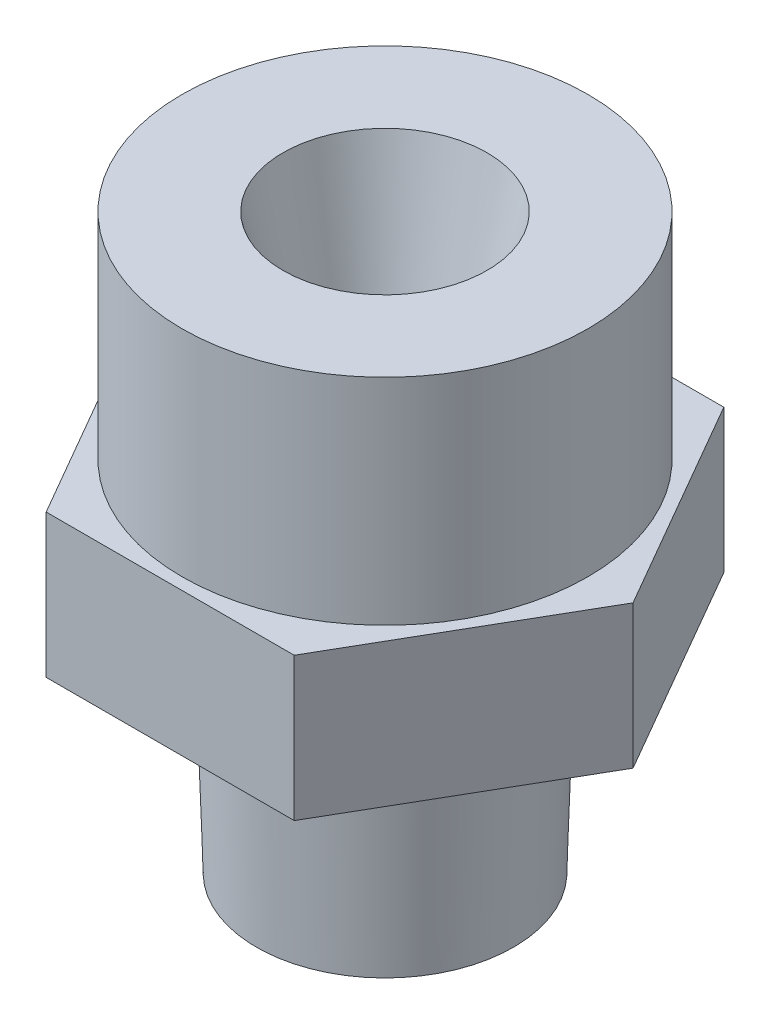
SolidWorks part; units mm, degrees
material "AISI 316 Annealed Stainless Steel Bar (SS)"
ref_plane "Front Plane" through (0, 0, 0) normal (0, 0, 1) x (1, 0, 0)
ref_plane "Top Plane" through (0, 0, 0) normal (0, 1, 0) x (1, 0, 0)
ref_plane "Right Plane" through (0, 0, 0) normal (1, 0, 0) x (0, 0, -1)
sketch "Sketch1" plane through (0, 0, 0) normal (0, 1, 0) x (1, 0, 0)
  circle A1 centre (0, 0) radius 9
  dimension "D2" = 18
extrude "Boss-Extrude1" add sketch "Sketch1" along normal blind 9.525
sketch "Sketch4" plane through (0, 0, 0) normal (0, -1, 0) x (1, 0, 0)
  circle A0 centre (0, 0) radius 3.175
  dimension "D1" = 6.35
extrude "Cut-Extrude1" cut sketch "Sketch4" against normal blind 3.175
sketch "Sketch5" plane through (0, 3.175, 0) normal (0, -1, 0) x (-1, 0, 0)
  circle A0 centre (0, 0) radius 3.175
  circle A1 centre (0, 0) radius 3.175 construction
extrude "Cut-Extrude2" cut sketch "Sketch5" against normal through all draft 12 draft outward yes
sketch "Sketch6" plane through (0, 0, 0) normal (0, -1, 0) x (1, 0, 0)
  line L1 (-10.9985, 0) -> (-5.4993, -9.525)
  line L2 (-5.4993, -9.525) -> (5.4993, -9.525)
  line L3 (5.4993, -9.525) -> (10.9985, 0)
  line L4 (10.9985, 0) -> (5.4993, 9.525)
  line L5 (5.4993, 9.525) -> (-5.4993, 9.525)
  line L6 (-5.4993, 9.525) -> (-10.9985, 0)
  circle A0 centre (0, 0) radius 9.525 construction
  circle A1 centre (0, 0) radius 3.175
  circle A2 centre (0, 0) radius 3.175 construction
  point P12 (0, 0)
  point P13 (0, 0)
  dimension "D1" = 19.05
extrude "Boss-Extrude3" add sketch "Sketch6" along normal blind 6.35
sketch "Sketch7" plane through (0, -6.35, 0) normal (0, -1, 0) x (1, 0, 0)
  circle A3 centre (0, 0) radius 6
  dimension "D1" = 12
extrude "Boss-Extrude4" add sketch "Sketch7" along normal blind 9.525 draft 1.79
sketch "Sketch8" plane through (0, -15.875, 0) normal (0, -1, 0) x (1, 0, 0)
  circle A0 centre (0, 0) radius 3.175
  dimension "D1" = 6.35
extrude "Cut-Extrude3" cut sketch "Sketch8" against normal through all
